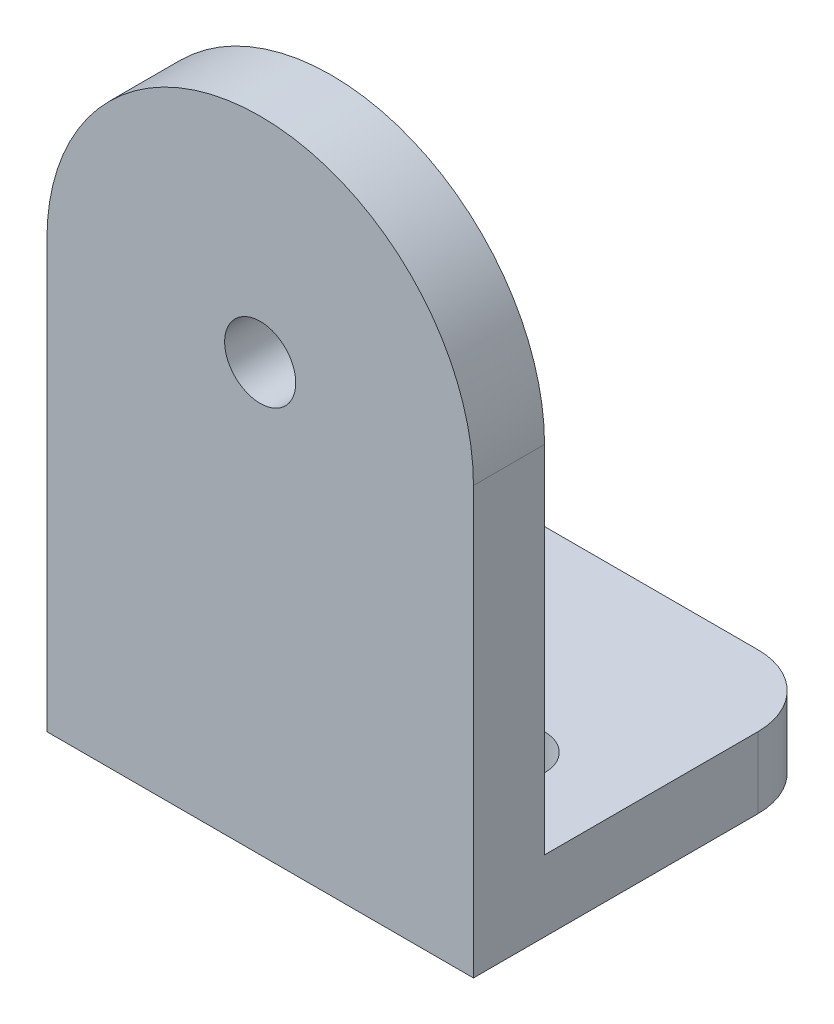
SolidWorks part; units mm, degrees
ref_plane "Ön Düzlem" through (0, 0, 0) normal (0, 0, 1) x (1, 0, 0)
ref_plane "Üst Düzlem" through (0, 0, 0) normal (0, 1, 0) x (1, 0, 0)
ref_plane "Sağ Düzlem" through (0, 0, 0) normal (1, 0, 0) x (0, 0, -1)
sketch "Çizim1" plane through (0, 0, 0) normal (0, 0, 1) x (1, 0, 0)
  line L0 (-30.9497, 7.3015) -> (-30.9497, -22.6985)
  line L1 (-30.9497, -22.6985) -> (-0.9497, -22.6985)
  line L2 (-0.9497, -22.6985) -> (-0.9497, 7.3015)
  circle A0 centre (-15.9497, 7.3015) radius 2.5
  arc A1 (-0.9497, 7.3015) -> (-30.9497, 7.3015) centre (-15.9497, 7.3015) ccw
  dimension "D1" = 5
  dimension "D2" = 30
  dimension "D3" = 30
extrude "Yükseklik-Ekstrüzyon1" add sketch "Çizim1" along normal blind 25
sketch "Çizim2" plane through (0, 0, 0) normal (1, 0, 0) x (0, 0, -1)
  line L0 (0, 22.3015) -> (-25, 22.3015) construction
  line L2 (0, -17.6985) -> (0, 22.3015)
  line L3 (0, 22.3015) -> (-20, 22.3015)
  line L4 (-20, -17.6985) -> (-20, 22.3015)
  line L5 (-20, -17.6985) -> (0, -17.6985)
extrude "Kes-Ekstrüzyon1" cut sketch "Çizim2" against normal blind 47
fillet "Radyus1" radius 5 2 edges at (-30.9497, -20.1985, 0) (-0.9497, -20.1985, 0)
sketch "Çizim3" plane through (0, 0, 0) normal (0, 1, 0) x (1, 0, 0)
  line L0 (-15.9497, 0) -> (-15.9497, -20) construction
  line L1 (-25.9497, 0) -> (-5.9497, 0) construction
  line L2 (-30.9497, -20) -> (-0.9497, -20) construction
  circle A0 centre (-23.4497, -15) radius 2.5
  circle A1 centre (-8.4497, -15) radius 2.5
  dimension "D1" = 5
  dimension "D2" = 5
  dimension "D3" = 15
  dimension "D4" = 15
extrude "Kes-Ekstrüzyon3" cut sketch "Çizim3" against normal blind 47
